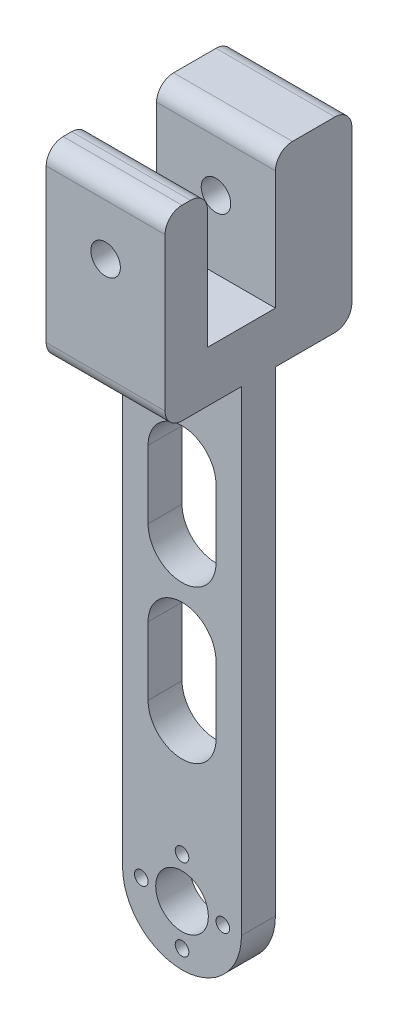
SolidWorks part; units mm, degrees
ref_plane "Front Plane" through (0, 0, 0) normal (0, 0, 1) x (1, 0, 0)
ref_plane "Top Plane" through (0, 0, 0) normal (0, 1, 0) x (1, 0, 0)
ref_plane "Right Plane" through (0, 0, 0) normal (1, 0, 0) x (0, 0, -1)
sketch "Sketch2" plane through (0, 0, 0) normal (0, 0, 1) x (1, 0, 0)
  line L1 (17.5, 97.5) -> (-17.5, 97.5)
  line L2 (17.5, 97.5) -> (17.5, -97.5)
  line L4 (-17.5, 97.5) -> (-17.5, -97.5)
  line L5 (17.5, 97.5) -> (-17.5, -97.5) construction
  line L6 (17.5, -97.5) -> (-17.5, 97.5) construction
  arc A0 (-17.5, -97.5) -> (17.5, -97.5) centre (0, -97.5) ccw
  point P0 (0, 0)
  dimension "D1" = 35
  dimension "D2" = 195
extrude "Boss-Extrude1" add sketch "Sketch2" along normal mid plane 10
sketch "Sketch3" plane through (0, 0, 0) normal (1, 0, 0) x (0, 0, -1)
  line L0 (0, 89.0588) -> (0, -106.455) construction
  line L2 (-22.5, 97.5) -> (22.5, 97.5)
  line L3 (-27.5, 92.5) -> (-27.5, 47.5)
  line L4 (-22.5, 42.5) -> (22.5, 42.5)
  line L5 (27.5, 92.5) -> (27.5, 47.5)
  line L6 (-27.5, 97.5) -> (27.5, 42.5) construction
  line L7 (-27.5, 42.5) -> (27.5, 97.5) construction
  line L8 (-5, 97.5) -> (5, 97.5) construction
  arc A0 (-27.5, 92.5) -> (-22.5, 97.5) centre (-22.5, 92.5) cw
  arc A1 (27.5, 92.5) -> (22.5, 97.5) centre (22.5, 92.5) ccw
  arc A2 (27.5, 47.5) -> (22.5, 42.5) centre (22.5, 47.5) cw
  arc A3 (-22.5, 42.5) -> (-27.5, 47.5) centre (-22.5, 47.5) cw
  point P3 (0, 70)
  dimension "D3" = 5
  dimension "D1" = 55
  dimension "D2" = 55
extrude "Boss-Extrude2" add sketch "Sketch3" along normal mid plane 35
sketch "Sketch4" plane through (-17.5, 0, 0) normal (-1, 0, 0) x (0, 0, 1)
  line L1 (22.5, 97.5) -> (-22.5, 97.5) construction
  line L3 (-5, 92.5) -> (-5, 57.5)
  line L4 (-5, 57.5) -> (15, 57.5)
  line L5 (15, 57.5) -> (15, 92.5)
  line L8 (-10, 97.5) -> (20, 97.5)
  arc A0 (-5, 92.5) -> (-10, 97.5) centre (-10, 92.5) ccw
  arc A1 (15, 92.5) -> (20, 97.5) centre (20, 92.5) cw
  dimension "D1" = 5
  dimension "D2" = 35
extrude "Cut-Extrude1" cut sketch "Sketch4" against normal up to surface (35 mm away) up to face at (17.5, 37.5, 0)
sketch "Sketch13" plane through (0, 0, -27.5) normal (0, 0, -1) x (-1, 0, 0)
  line L0 (-17.5, 92.5) -> (17.5, 92.5) construction
  circle A0 centre (0, 77.5) radius 4.35
  dimension "D2" = 8.7
  dimension "D1" = 15
extrude "Cut-Extrude7" cut sketch "Sketch13" against normal through all
sketch "Sketch5" plane through (0, 0, 5) normal (0, 0, 1) x (1, 0, 0)
  line L0 (0, 13.7562) -> (0, -6.2438) construction
  line L1 (10, 13.7562) -> (10, -6.2438)
  line L2 (-10, 13.7562) -> (-10, -6.2438)
  line L3 (0, -31.2438) -> (0, -51.2438) construction
  line L4 (10, -31.2438) -> (10, -51.2438)
  line L5 (-10, -31.2438) -> (-10, -51.2438)
  arc A0 (10, 13.7562) -> (-10, 13.7562) centre (0, 13.7562) ccw
  arc A1 (-10, -6.2438) -> (10, -6.2438) centre (0, -6.2438) ccw
  arc A2 (10, -31.2438) -> (-10, -31.2438) centre (0, -31.2438) ccw
  arc A3 (-10, -51.2438) -> (10, -51.2438) centre (0, -51.2438) ccw
  point P3 (0, 3.7562)
  point P10 (0, -41.2438)
  dimension "D3" = 2
  dimension "D1" = 20
  dimension "D2" = 20
extrude "Cut-Extrude2" cut sketch "Sketch5" against normal blind 10
mirror "Mirror1" about plane through (0, 0, 0) normal (0, 0, 1) of "Cut-Extrude2"
sketch "Sketch8" plane through (0, 0, 5) normal (0, 0, 1) x (1, 0, 0)
  line L0 (0, 23.7562) -> (0, -16.2438) construction
  line L1 (-10, 3.7562) -> (10, 3.7562) construction
  line L2 (-10, 13.7562) -> (-10, -6.2438) construction
  line L3 (10, -6.2438) -> (10, 13.7562) construction
  line L4 (0, 13.7562) -> (0, -6.2438) construction
  line L5 (5, 13.7562) -> (5, -6.2438)
  line L6 (-5, 13.7562) -> (-5, -6.2438)
  line L7 (-5, -31.2438) -> (-5, -51.2438)
  line L8 (5, -31.2438) -> (5, -51.2438)
  line L9 (0, -31.2438) -> (0, -51.2438) construction
  arc A0 (10, 13.7562) -> (-10, 13.7562) centre (0, 13.7562) ccw construction
  arc A1 (-10, -6.2438) -> (10, -6.2438) centre (0, -6.2438) ccw construction
  arc A2 (5, 13.7562) -> (-5, 13.7562) centre (0, 13.7562) ccw
  arc A3 (-5, -6.2438) -> (5, -6.2438) centre (0, -6.2438) ccw
  arc A4 (5, -31.2438) -> (-5, -31.2438) centre (0, -31.2438) ccw
  arc A5 (-5, -51.2438) -> (5, -51.2438) centre (0, -51.2438) ccw
  point P16 (0, 3.7562)
  point P25 (0, -41.2438)
  dimension "D1" = 20
  dimension "D2" = 10
  dimension "D3" = 2
extrude "Cut-Extrude3" cut sketch "Sketch8" against normal blind 10
sketch "Sketch9" plane through (0, 0, -5) normal (0, 0, -1) x (-1, 0, 0)
  line L0 (-17.5, -97.5) -> (17.5, -97.5) construction
  circle A0 centre (0, -97.5) radius 7.75
  circle A1 centre (12, -97.5) radius 2
  circle A3 centre (0, -109.5) radius 2
  circle A4 centre (-12, -97.5) radius 2
  circle A5 centre (0, -85.5) radius 2
  arc A6 (-17.5, -97.5) -> (17.5, -97.5) centre (0, -97.5) ccw construction
  point P14 (0, -97.5)
  dimension "D1" = 15.5
  dimension "D3" = 4
  dimension "D2" = 12
  dimension "D5" = 17.5
  dimension "D4" = 4
extrude "Cut-Extrude4" cut sketch "Sketch9" against normal through all
